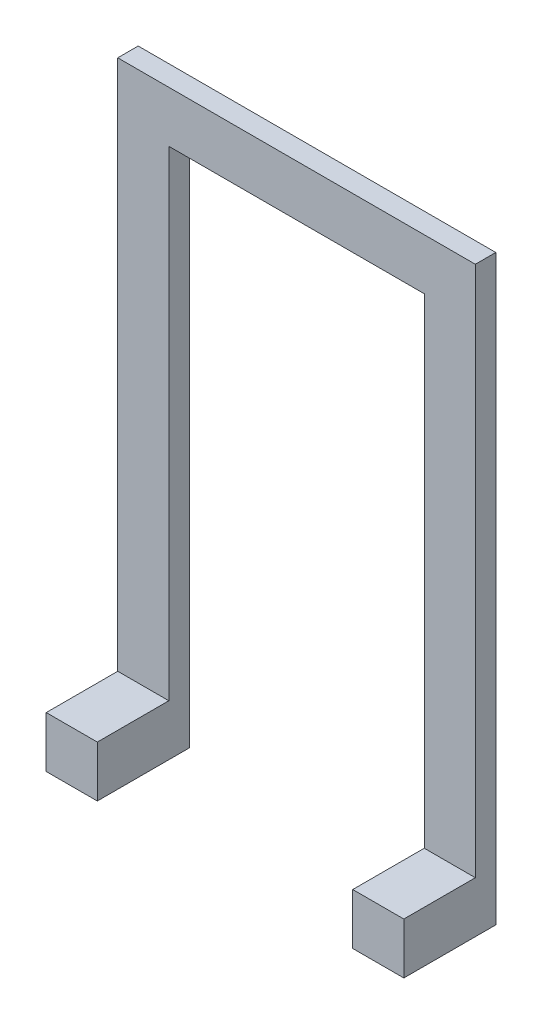
SolidWorks part; units mm, degrees
ref_plane "Front Plane" through (0, 0, 0) normal (0, 0, 1) x (1, 0, 0)
ref_plane "Top Plane" through (0, 0, 0) normal (0, 1, 0) x (1, 0, 0)
ref_plane "Right Plane" through (0, 0, 0) normal (1, 0, 0) x (0, 0, -1)
sketch "Sketch1" plane through (0, 0, 0) normal (0, 0, 1) x (1, 0, 0)
  line L9 (-8.75, -17.25) -> (-6.25, -17.25)
  line L10 (-8.75, -17.25) -> (-8.75, 8.75)
  line L11 (-8.75, 8.75) -> (-6.25, 8.75)
  line L12 (-6.25, -17.25) -> (-6.25, 8.75)
  line L13 (6.25, -17.25) -> (8.75, -17.25)
  line L14 (6.25, -17.25) -> (6.25, 8.75)
  line L15 (6.25, 8.75) -> (8.75, 8.75)
  line L16 (8.75, -17.25) -> (8.75, 8.75)
  line L17 (-8.75, 8.75) -> (8.75, 8.75)
  line L18 (-8.75, 8.75) -> (-8.75, 11.25)
  line L19 (-8.75, 11.25) -> (8.75, 11.25)
  line L20 (8.75, 8.75) -> (8.75, 11.25)
  point P11 (12.0477, 12.3482)
  point P12 (-8.7847, 34.5427)
  dimension "D1" = 17.5
  dimension "D2" = 2.5
  dimension "D3" = 2.5
  dimension "D4" = 2.5
  dimension "D5" = 26
  dimension "D6" = 26
  dimension "D7" = 8.75
  dimension "D8" = 11.25
extrude "Boss-Extrude1" add sketch "Sketch1" along normal blind 1 contours L9 L12 L11 L10 | L15 L20 L19 L18 L11 L17 | L13 L16 L15 L14
sketch "Sketch2" plane through (0, 0, 1) normal (0, 0, 1) x (1, 0, 0)
  line L0 (-8.75, -17.25) -> (-8.75, 11.25) construction
  line L1 (-6.25, -17.25) -> (-8.75, -17.25)
  line L2 (-6.25, -17.25) -> (-6.25, -14.75)
  line L3 (-6.25, -14.75) -> (-8.75, -14.75)
  line L4 (-8.75, -17.25) -> (-8.75, -14.75)
  line L5 (8.75, -17.25) -> (8.75, 11.25) construction
  line L6 (6.25, -17.25) -> (8.75, -17.25)
  line L7 (6.25, -17.25) -> (6.25, -14.75)
  line L8 (6.25, -14.75) -> (8.75, -14.75)
  line L9 (8.75, -17.25) -> (8.75, -14.75)
  dimension "D1" = 2.5
extrude "Boss-Extrude2" add sketch "Sketch2" along normal blind 3.5
